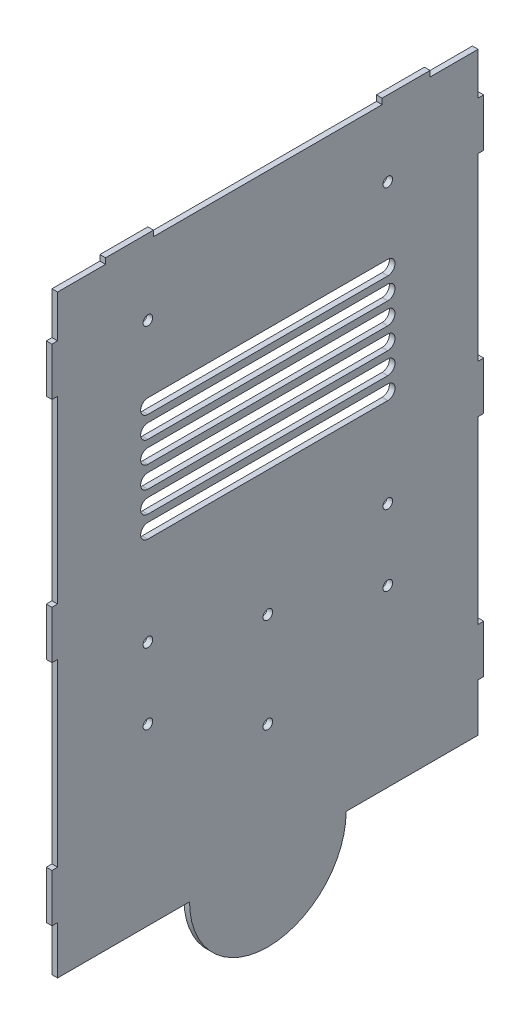
SolidWorks part; units mm, degrees
ref_plane "Front Plane" through (0, 0, 0) normal (0, 0, 1) x (1, 0, 0)
ref_plane "Top Plane" through (0, 0, 0) normal (0, 1, 0) x (1, 0, 0)
ref_plane "Right Plane" through (0, 0, 0) normal (1, 0, 0) x (0, 0, -1)
sketch "Sketch1" plane through (0, 0, 0) normal (1, 0, 0) x (0, 0, -1)
  line L0 (-130.1329, 199.8003) -> (-130.1329, 182.1625)
  line L4 (-132.4951, 182.1625) -> (-132.4951, 162.1625)
  line L5 (-130.1329, 182.1625) -> (-132.4951, 182.1625)
  line L6 (47.5049, 182.1625) -> (47.5049, 162.1625)
  line L7 (45.1427, 199.8003) -> (45.1427, 182.1625)
  line L8 (45.1427, 182.1625) -> (47.5049, 182.1625)
  line L9 (-132.4951, 162.1625) -> (-130.1329, 162.1625)
  line L10 (-130.1329, 162.1625) -> (-130.1329, 87.1625)
  line L11 (-130.1329, 87.1625) -> (-132.4951, 87.1625)
  line L12 (-132.4951, 87.1625) -> (-132.4951, 67.1625)
  line L13 (-132.4951, 67.1625) -> (-130.1329, 67.1625)
  line L14 (-130.1329, 67.1625) -> (-130.1329, -7.8375)
  line L15 (-130.1329, -47.8375) -> (-130.1329, -27.8375)
  line L16 (-130.1329, -27.8375) -> (-132.4951, -27.8375)
  line L17 (-132.4951, -27.8375) -> (-132.4951, -7.8375)
  line L18 (-132.4951, -7.8375) -> (-130.1329, -7.8375)
  line L19 (47.5049, 162.1625) -> (45.1427, 162.1625)
  line L20 (45.1427, 162.1625) -> (45.1427, 87.1625)
  line L21 (45.1427, 87.1625) -> (47.5049, 87.1625)
  line L22 (47.5049, 87.1625) -> (47.5049, 67.1625)
  line L23 (47.5049, 67.1625) -> (45.1427, 67.1625)
  line L24 (45.1427, 67.1625) -> (45.1427, -7.8375)
  line L25 (45.1427, -7.8375) -> (47.5049, -7.8375)
  line L26 (47.5049, -7.8375) -> (47.5049, -27.8375)
  line L27 (47.5049, -27.8375) -> (45.1427, -27.8375)
  line L28 (45.1427, -27.8375) -> (45.1427, -47.8375)
  line L29 (-130.1329, 199.8003) -> (-110.1329, 199.8003)
  line L30 (-110.1329, 199.8003) -> (-110.1329, 202.1625)
  line L31 (-110.1329, 202.1625) -> (-90.1329, 202.1625)
  line L32 (-90.1329, 202.1625) -> (-90.1329, 199.8003)
  line L33 (-90.1329, 199.8003) -> (5.1427, 199.8003)
  line L34 (5.1427, 199.8003) -> (5.1427, 202.1625)
  line L35 (5.1427, 202.1625) -> (25.1427, 202.1625)
  line L36 (25.1427, 202.1625) -> (25.1427, 199.8003)
  line L37 (25.1427, 199.8003) -> (45.1427, 199.8003)
  line L38 (-130.1329, -47.8375) -> (-75.1329, -47.8375)
  line L40 (-9.8573, -47.8375) -> (45.1427, -47.8375)
  arc A1 (-9.8573, -47.8375) -> (-75.1329, -47.8375) centre (-42.4951, -47.8375) cw
  dimension "D2" = 175.2756
  dimension "D3" = 2.3622
  dimension "D4" = 2.3622
  dimension "D5" = 20
  dimension "D6" = 20
  dimension "D7" = 75
  dimension "D8" = 75
  dimension "D9" = 2.3622
  dimension "D10" = 2.3622
  dimension "D11" = 20
  dimension "D12" = 75
  dimension "D13" = 20
  dimension "D14" = 20
  dimension "D15" = 2.3622
  dimension "D16" = 2.3622
  dimension "D17" = 20
  dimension "D18" = 20
  dimension "D19" = 75
  dimension "D20" = 2.3622
  dimension "D21" = 2.3622
  dimension "D22" = 20
  dimension "D23" = 2.3622
  dimension "D24" = 2.3622
  dimension "D25" = 2.3622
  dimension "D26" = 2.3622
  dimension "D27" = 20
  dimension "D28" = 20
  dimension "D29" = 20
  dimension "D30" = 20
  dimension "D31" = 2.3622
  dimension "D32" = 2.3622
  dimension "D33" = 55
  dimension "D34" = 90
  dimension "D35" = 55
  dimension "D36" = 0
extrude "Boss-Extrude1" add sketch "Sketch1" along normal blind 2.3622
sketch "Sketch2" plane through (2.3622, 0, 0) normal (1, 0, 0) x (0, 0, -1)
  line L0 (-92.4951, 139.8003) -> (7.5049, 139.8003) construction
  line L1 (-92.4951, 142.8003) -> (7.5049, 142.8003)
  line L2 (-92.4951, 136.8003) -> (7.5049, 136.8003)
  line L3 (-92.4951, 130.8003) -> (7.5049, 130.8003) construction
  line L4 (-92.4951, 133.8003) -> (7.5049, 133.8003)
  line L5 (-92.4951, 127.8003) -> (7.5049, 127.8003)
  line L6 (-92.4951, 121.8003) -> (7.5049, 121.8003) construction
  line L7 (-92.4951, 124.8003) -> (7.5049, 124.8003)
  line L8 (-92.4951, 118.8003) -> (7.5049, 118.8003)
  line L9 (-92.4951, 112.8003) -> (7.5049, 112.8003) construction
  line L10 (-92.4951, 115.8003) -> (7.5049, 115.8003)
  line L11 (-92.4951, 109.8003) -> (7.5049, 109.8003)
  line L12 (-92.4951, 103.8003) -> (7.5049, 103.8003) construction
  line L13 (-92.4951, 106.8003) -> (7.5049, 106.8003)
  line L14 (-92.4951, 100.8003) -> (7.5049, 100.8003)
  line L15 (-92.4951, 94.8003) -> (7.5049, 94.8003) construction
  line L16 (-92.4951, 97.8003) -> (7.5049, 97.8003)
  line L17 (-92.4951, 91.8003) -> (7.5049, 91.8003)
  line L19 (5.1427, 199.8003) -> (-90.1329, 199.8003) construction
  arc A0 (-92.4951, 142.8003) -> (-92.4951, 136.8003) centre (-92.4951, 139.8003) ccw
  arc A1 (7.5049, 136.8003) -> (7.5049, 142.8003) centre (7.5049, 139.8003) ccw
  arc A2 (-92.4951, 133.8003) -> (-92.4951, 127.8003) centre (-92.4951, 130.8003) ccw
  arc A3 (7.5049, 127.8003) -> (7.5049, 133.8003) centre (7.5049, 130.8003) ccw
  arc A4 (-92.4951, 124.8003) -> (-92.4951, 118.8003) centre (-92.4951, 121.8003) ccw
  arc A5 (7.5049, 118.8003) -> (7.5049, 124.8003) centre (7.5049, 121.8003) ccw
  arc A6 (-92.4951, 115.8003) -> (-92.4951, 109.8003) centre (-92.4951, 112.8003) ccw
  arc A7 (7.5049, 109.8003) -> (7.5049, 115.8003) centre (7.5049, 112.8003) ccw
  arc A8 (-92.4951, 106.8003) -> (-92.4951, 100.8003) centre (-92.4951, 103.8003) ccw
  arc A9 (7.5049, 100.8003) -> (7.5049, 106.8003) centre (7.5049, 103.8003) ccw
  arc A10 (-92.4951, 97.8003) -> (-92.4951, 91.8003) centre (-92.4951, 94.8003) ccw
  arc A11 (7.5049, 91.8003) -> (7.5049, 97.8003) centre (7.5049, 94.8003) ccw
  circle A12 centre (-92.4951, 54.5966) radius 2
  circle A13 centre (7.5049, 54.5966) radius 2
  circle A14 centre (7.5049, 25.043) radius 2
  circle A15 centre (-92.4951, 170.7711) radius 2
  circle A16 centre (7.5049, 170.7711) radius 2
  circle A17 centre (-92.4951, 25.043) radius 2
  circle A18 centre (-42.4951, 39.5467) radius 2
  circle A19 centre (-42.4951, 0) radius 2
  point P2 (-42.4951, 139.8003)
  point P10 (-42.4951, 130.8003)
  point P17 (-42.4951, 121.8003)
  point P24 (-42.4951, 112.8003)
  point P31 (-42.4951, 103.8003)
  point P38 (-42.4951, 94.8003)
  point P48 (-42.4951, 199.8003)
  point P61 (-102.4951, 54.5966)
  point P62 (-2.4951, 50.8238)
  point P63 (-2.4951, 54.5966)
  point P64 (-2.4951, 25.043)
  point P65 (-102.4951, 25.043)
  point P66 (-102.4951, 150.9951)
  point P67 (-2.4951, 150.9951)
  point P68 (-52.4951, 40.1656)
  point P69 (-52.4951, 0)
  point P70 (0, 0)
  point P71 (0, 0)
  point P72 (-92.4951, 54.5966)
  point P73 (-92.4951, 25.043)
  point P74 (7.5049, 25.043)
  point P75 (7.5049, 54.5966)
  point P76 (-42.4951, 39.5467)
  point P77 (-42.4951, 0)
  point P78 (7.5049, 170.7711)
  point P79 (-92.4951, 170.7711)
  dimension "D2" = 3
  dimension "D5" = 4
  dimension "D1" = 100
  dimension "D4" = 60
  dimension "D3" = 6
extrude "Cut-Extrude1" cut sketch "Sketch2" against normal through all
